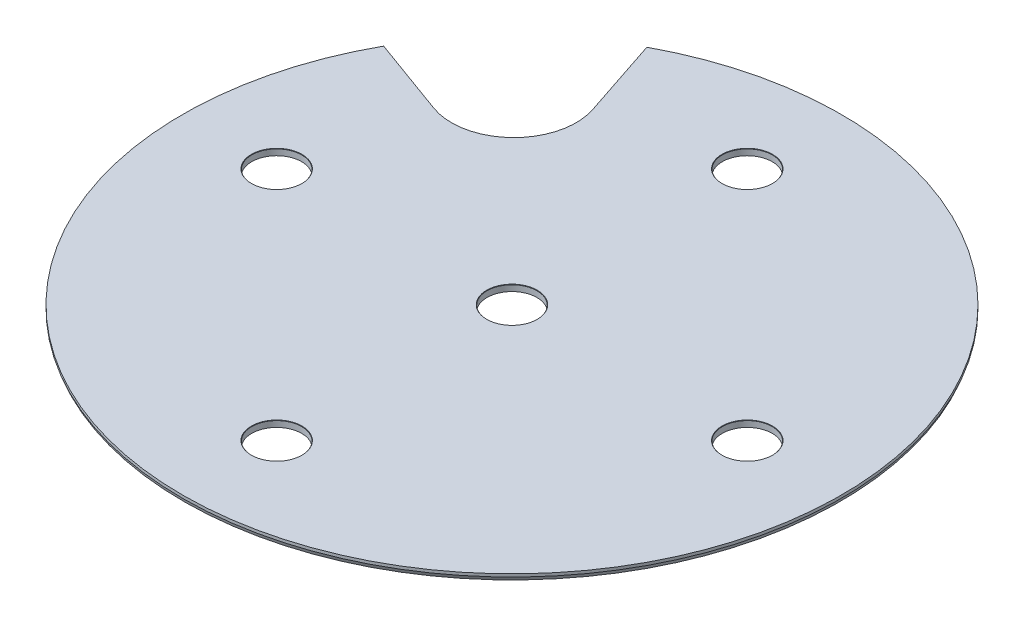
SolidWorks part; units mm, degrees
ref_plane "Front Plane" through (0, 0, 0) normal (0, 0, 1) x (1, 0, 0)
ref_plane "Top Plane" through (0, 0, 0) normal (0, 1, 0) x (1, 0, 0)
ref_plane "Right Plane" through (0, 0, 0) normal (1, 0, 0) x (0, 0, -1)
sketch "Sketch1" plane through (0, 0, 0) normal (0, 1, 0) x (1, 0, 0)
  circle A0 centre (0, 0) radius 26.4
  dimension "D1" = 52.8
extrude "Boss-Extrude1" add sketch "Sketch1" along normal blind 0.5 contours A0
sketch "Sketch2" plane through (0, 0.5, 0) normal (0, 1, 0) x (1, 0, 0)
  circle A0 centre (0, 0) radius 21.8
  circle A1 centre (-18.85, 0) radius 2.95 construction
  circle A2 centre (0, 18.85) radius 2.95 construction
  circle A3 centre (18.85, 0) radius 2.95 construction
  circle A4 centre (0, -18.85) radius 2.95 construction
  point P3 (-18.85, 0)
  point P8 (0, 18.85)
  point P10 (18.85, 0)
  point P12 (0, -18.85)
  point P14 (0, 0)
  dimension "D1" = 43.6
  dimension "D2" = 5.9
  dimension "D3" = 4
hole_wizard "Ø4.0 (4) Diameter Hole1" positions "Sketch2" profile "Sketch4" hole size "Ø4.0" standard "ANSI Metric" end condition through all
sketch "Sketch4" plane through (0, 0.5, 0) normal (1, 0, 0) x (0, 0, 1)
  line L0 (0, 0) -> (0, 0.5)
  line L1 (0, 0.5) -> (2, 0.5)
  line L2 (2, 0.5) -> (2, 0.0273)
  line L3 (2, 0.0273) -> (2.025, 0)
  line L5 (2.025, 0) -> (0, 0)
  line L6 (-2, 0.0273) -> (-2.025, 0) construction
  line L11 (0, -6.35) -> (0, 107.95) construction
  dimension "Thru Hole Dia." = 4
  dimension "Thru Hole Depth" = 0.5
  dimension "Near C'Sink Dia." = 4.05
  dimension "Near C'Sink Angle" = 85
chamfer "Chamfer1" distance 0.1 angle 70 1 edges at (0, 0, 26.4)
sketch "Sketch5" plane through (0, 0.5, 0) normal (0, 1, 0) x (1, 0, 0)
  line L0 (-23.0864, 12.8054) -> (-7.0554, 6.9802)
  line L1 (-7.0554, 6.9802) -> (-12.4661, 23.2714)
  circle A0 centre (0, 0) radius 26.4 construction
  circle A1 centre (-15.0564, 15.2074) radius 5
  circle M9 centre (0, 0) radius 26.4
  dimension "D1" = 10
extrude "Cut-Extrude1" cut sketch "Sketch5" against normal through all contours A1 | A1 L0 M9 | A1 L1 M9
